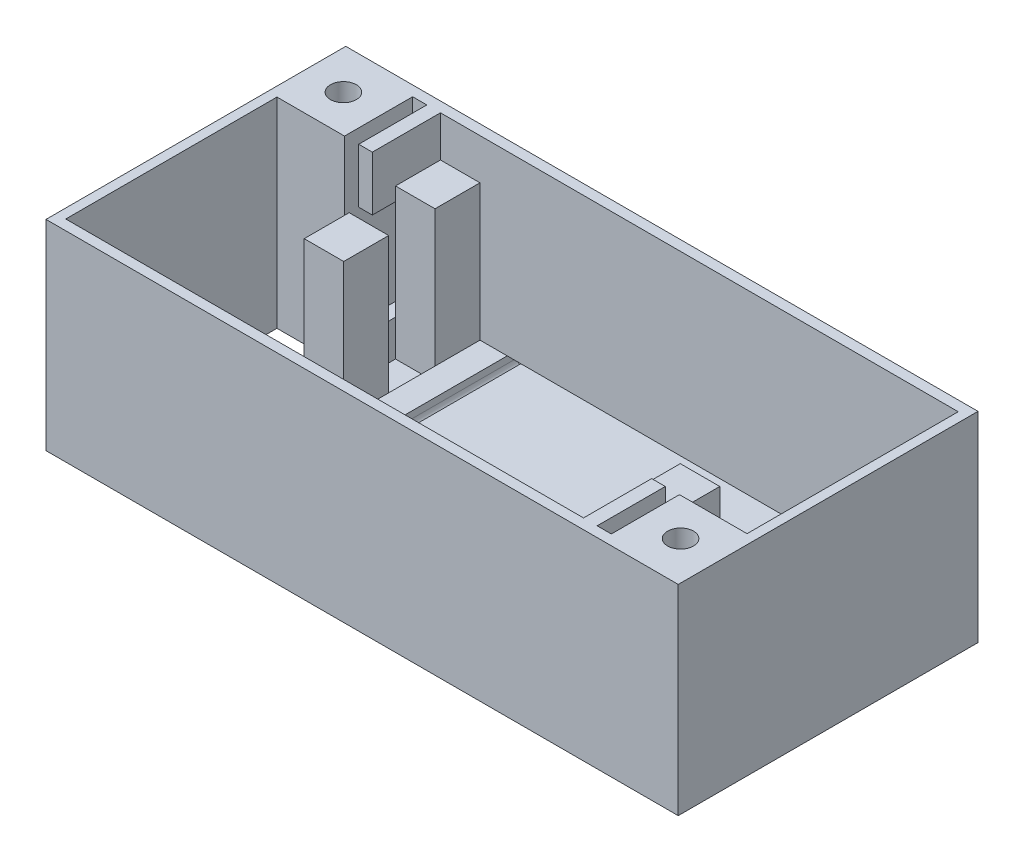
SolidWorks part; units mm, degrees
ref_plane "Plano frontal" through (0, 0, 0) normal (0, 0, 1) x (1, 0, 0)
ref_plane "Plano superior" through (0, 0, 0) normal (0, 1, 0) x (1, 0, 0)
ref_plane "Plano direito" through (0, 0, 0) normal (1, 0, 0) x (0, 0, -1)
sketch "Esboço1" plane through (0, 0, 0) normal (0, 1, 0) x (1, 0, 0)
  line L1 (-23.2, 11) -> (23.2, 11)
  line L2 (-23.2, 11) -> (-23.2, -11)
  line L3 (-23.2, -11) -> (23.2, -11)
  line L4 (23.2, 11) -> (23.2, -11)
  line L5 (-23.2, 11) -> (23.2, -11) construction
  line L6 (-23.2, -11) -> (23.2, 11) construction
  line L7 (-22.5, 10.25) -> (22.5, 10.25)
  line L8 (-22.5, 10.25) -> (-22.5, -10.25)
  line L9 (-22.5, -10.25) -> (22.5, -10.25)
  line L10 (22.5, 10.25) -> (22.5, -10.25)
  line L11 (-22.5, 10.25) -> (22.5, -10.25) construction
  line L12 (-22.5, -10.25) -> (22.5, 10.25) construction
  point P0 (0, 0)
  point P6 (0, 0)
  dimension "D1" = 22
  dimension "D2" = 46.4
  dimension "D3" = 20.5
  dimension "D4" = 45
extrude "Ressalto-extrusão1" add sketch "Esboço1" along normal blind 14
sketch "Esboço2" plane through (0, 0, 0) normal (0, 1, 0) x (1, 0, 0)
  line L1 (-23.2, 11) -> (23.2, 11)
  line L2 (-23.2, 11) -> (-23.2, -11)
  line L3 (-23.2, -11) -> (23.2, -11)
  line L4 (23.2, 11) -> (23.2, -11)
  line L5 (-23.2, 11) -> (23.2, -11) construction
  line L6 (-23.2, -11) -> (23.2, 11) construction
  point P0 (0, 0)
extrude "Ressalto-extrusão2" add sketch "Esboço2" against normal blind 0.7
sketch "Esboço3" plane through (0, 0, 0) normal (0, 1, 0) x (1, 0, 0)
  line L0 (22.5, 10.25) -> (-22.5, 10.25) construction
  line L9 (-15.5, 0.25) -> (-12.6, 0.25)
  line L14 (-15.5, 0.25) -> (-15.5, 3.55)
  line L15 (-15.5, 3.55) -> (-12.6, 3.55)
  line L16 (-12.6, 0.25) -> (-12.6, 3.55)
  line L17 (-15.5, 10.25) -> (-12.6, 10.25)
  line L18 (-15.5, 10.25) -> (-15.5, 6.95)
  line L19 (-15.5, 6.95) -> (-12.6, 6.95)
  line L20 (-12.6, 10.25) -> (-12.6, 6.95)
  line L22 (-22.5, -10.25) -> (22.5, -10.25) construction
  line L23 (15.5, -10.25) -> (12.6, -10.25)
  line L24 (15.5, -10.25) -> (15.5, -6.95)
  line L25 (15.5, -6.95) -> (12.6, -6.95)
  line L26 (12.6, -10.25) -> (12.6, -6.95)
  line L28 (12.6, -3.55) -> (15.5, -3.55)
  line L29 (12.6, -3.55) -> (12.6, -0.25)
  line L30 (12.6, -0.25) -> (15.5, -0.25)
  line L31 (15.5, -3.55) -> (15.5, -0.25)
  dimension "D1" = 7
  dimension "D3" = 2.9
  dimension "D4" = 3.3
  dimension "D5" = 3.3
  dimension "D6" = 2.9
  dimension "D7" = 2.9
  dimension "D8" = 2.9
  dimension "D9" = 7
  dimension "D10" = 3.3
  dimension "D11" = 3.3
  dimension "D12" = 10
  dimension "D13" = 10
extrude "Ressalto-extrusão3" add sketch "Esboço3" along normal blind 11
sketch "Esboço4" plane through (0, 0, -10.25) normal (0, 0, 1) x (1, 0, 0)
  line L0 (-23.2, 14) -> (23.2, 14) construction
  line L1 (-15.5, 14) -> (-16.5, 14)
  line L2 (-15.5, 14) -> (-15.5, 10)
  line L7 (-17.5425, 14) -> (-17.5425, 0)
  line L9 (-16.5, 14) -> (-16.5, 10)
  line L12 (-16.5, 10) -> (-15.5, 10)
  line L13 (-17.5425, 14) -> (-22.5, 14)
  line L14 (22.5, 14) -> (-22.5, 14) construction
  line L15 (-22.5, 14) -> (-22.5, 0)
  line L17 (-15.5, 0) -> (-15.5, 2.6609)
  line L18 (-15.5, 2.6609) -> (-16.5, 2.6609)
  line L20 (-22.5, 0) -> (-17.5336, 0)
  line L22 (-16.5, 2.6609) -> (-16.5, 0)
  line L24 (-16.5, 0) -> (-15.5, 0)
  line L25 (-15.5, 0) -> (-22.5, 0) construction
  line L26 (-15.5, 11) -> (-15.5, 0) construction
  line L27 (-22.5, 14) -> (-22.5, 0) construction
  line M6 (-22.5, 0) -> (-15.5, 0)
  line M7 (-15.5, 0) -> (-15.5, 11)
  line M12 (22.5, 14) -> (-22.5, 14)
extrude "Ressalto-extrusão4" add sketch "Esboço4" along normal blind 5 contours L15 L7 M12 M6 | L18 L22 M6 M7 | L9 L12 L2 L1
sketch "Esboço5" plane through (0, 0, 10.25) normal (0, 0, -1) x (-1, 0, 0)
  line L24 (23.2, 14) -> (-23.2, 14) construction
  line L25 (-17.54, 0) -> (-22.5, 0)
  line L26 (-17.54, 0) -> (-17.54, 14)
  line L27 (-17.54, 14) -> (-22.5, 14)
  line L28 (-22.5, 0) -> (-22.5, 14)
  line L29 (-15.5, 2.6609) -> (-16.5, 2.6609)
  line L30 (-15.5, 14) -> (-16.5, 14)
  line L31 (-15.5, 14) -> (-15.5, 10)
  line L32 (-15.5, 0) -> (-16.5, 0)
  line L33 (-16.5, 14) -> (-16.5, 10)
  line L34 (-15.5, 10) -> (-16.5, 10)
  line L35 (-15.5, 2.6609) -> (-15.5, 0)
  line L36 (-16.5, 2.6609) -> (-16.5, 0)
  line L37 (-22.5, 14) -> (-22.5, 0) construction
  line M14 (-22.5, 0) -> (-15.5, 0)
  line M15 (-15.5, 0) -> (-15.5, 11)
  line M20 (22.5, 14) -> (-22.5, 14)
  dimension "D4" = 1
  dimension "D5" = 1.04
extrude "Ressalto-extrusão5" add sketch "Esboço5" along normal blind 5 contours L34 L31 L33 M15 M20 | L29 L36 M14 M15 | L28 L27 L26 L25
sketch "Esboço10" plane through (0, 0, 0) normal (0, 1, 0) x (1, 0, 0)
  line L8 (15.5, 0.25) -> (-12.6, 0.25)
  line L10 (22.5, 10.25) -> (-12.6, 10.25)
  line L11 (-12.6, 0.25) -> (-12.6, 10.25)
  line L13 (15.5, 0.25) -> (15.5, -10.25)
  line L14 (15.5, -10.25) -> (22.5, -10.25)
  line L15 (22.5, 10.25) -> (22.5, -10.25)
  dimension "D1" = 10
extrude "Ressalto-extrusão9" add sketch "Esboço10" along normal blind 1
sketch "Esboço15" plane through (0, -0.7, 0) normal (0, -1, 0) x (1, 0, 0)
  line L0 (-22.5, -5.25) -> (-22.5, -0.25)
  line L5 (-22.5, -5.25) -> (-22.5, 10.25) construction
  line L7 (-17.5425, -5.25) -> (-17.5425, -0.25)
  line L8 (-17.5425, -0.25) -> (-22.5, -0.25)
  line L9 (22.5, 5.25) -> (17.54, 5.25)
  line L10 (22.5, 5.25) -> (22.5, 0.25)
  line L11 (22.5, 0.25) -> (17.54, 0.25)
  line L12 (17.54, 5.25) -> (17.54, 0.25)
  line L13 (-22.5, -5.25) -> (-17.5425, -5.25)
  dimension "D1" = 5
  dimension "D2" = 5
extrude "Corte-extrusão3" cut sketch "Esboço15" along normal mid plane 5
sketch "Esboço16" plane through (0, -0.7, 0) normal (0, -1, 0) x (1, 0, 0)
  circle A0 centre (-20.372, -8) radius 0.95
  circle A1 centre (20.372, 8) radius 0.95
  dimension "D1" = 1.9
  dimension "D2" = 1.9
  dimension "D3" = 3
  dimension "D4" = 2.828
  dimension "D5" = 3
  dimension "D6" = 2.828
extrude "Corte-extrusão4" cut sketch "Esboço16" against normal blind 4
sketch "Esboço18" plane through (0, 0, -0.25) normal (0, 0, 1) x (1, 0, 0)
  line L0 (-10.6, 0.5) -> (-10.6, 1)
  line L3 (-12.6, 1) -> (15.5, 1) construction
  line L4 (-9.6, 0.5) -> (-9.6, 1)
  line L5 (-10.6, 1) -> (-9.6, 1)
  arc A0 (-10.6, 0.5) -> (-9.6, 0.5) centre (-10.1, 0.5) ccw
  dimension "D1" = 2
extrude "Corte-extrusão7" cut sketch "Esboço18" against normal blind 11
sketch "Esboço19" plane through (0, 0, -11) normal (0, 0, -1) x (-1, 0, 0)
  line L0 (-12.6, 11) -> (-12.6, 0) construction
  line L2 (-22.5, 1) -> (9.6, 1) construction
  line L3 (-10.6, 0.5) -> (-10.6, 1)
  line L4 (-9.6, 0.5) -> (-9.6, 1)
  line L5 (-9.6, 1) -> (-10.6, 1)
  arc A0 (-10.6, 0.5) -> (-9.6, 0.5) centre (-10.1, 0.5) ccw
  dimension "D1" = 2
extrude "Corte-extrusão8" cut sketch "Esboço19" against normal blind 11
sketch "Esboço20" plane through (0, 14, 0) normal (0, 1, 0) x (1, 0, 0)
  circle A3 centre (20.372, -8) radius 0.95 construction
  circle A4 centre (-20.372, 8) radius 0.95 construction
  circle A5 centre (20.372, -8) radius 0.95
  circle A6 centre (-20.372, 8) radius 0.95
extrude "Corte-extrusão9" cut sketch "Esboço20" against normal blind 4
